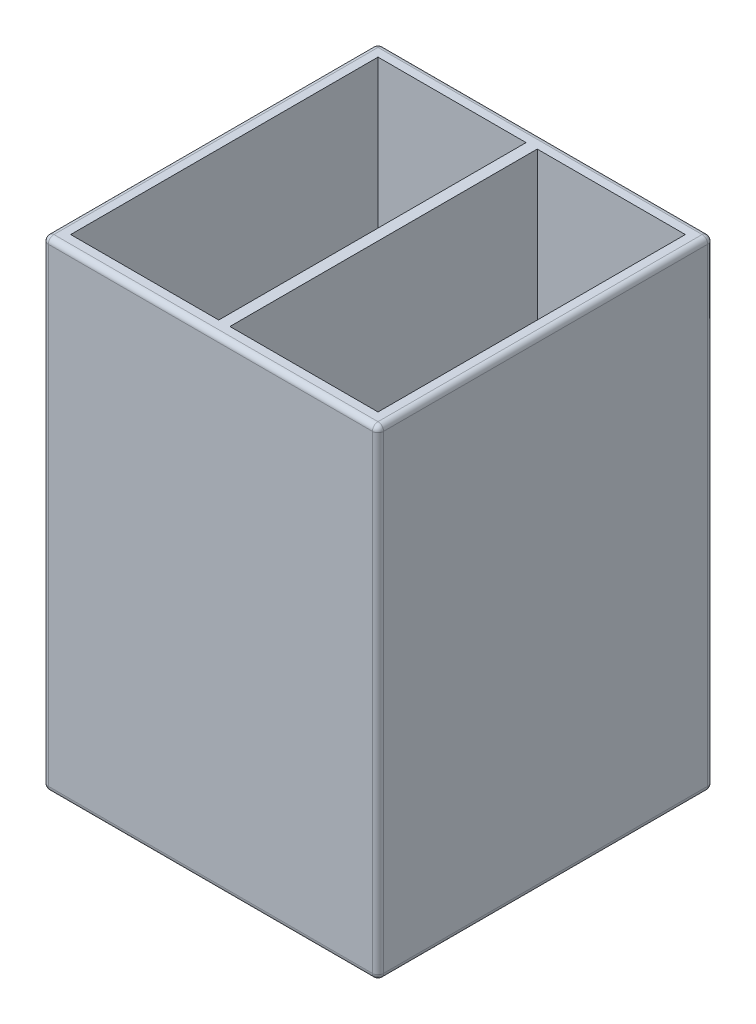
SolidWorks part; units mm, degrees
ref_plane "Front Plane" through (0, 0, 0) normal (0, 0, 1) x (1, 0, 0)
ref_plane "Top Plane" through (0, 0, 0) normal (0, 1, 0) x (1, 0, 0)
ref_plane "Right Plane" through (0, 0, 0) normal (1, 0, 0) x (0, 0, -1)
sketch "Sketch3" plane through (0, 0, 0) normal (0, 1, 0) x (1, 0, 0)
  line L1 (-164.0002, 4.2753) -> (-87.8002, 4.2753)
  line L2 (-164.0002, 4.2753) -> (-164.0002, -71.9247)
  line L3 (-164.0002, -71.9247) -> (-87.8002, -71.9247)
  line L4 (-87.8002, 4.2753) -> (-87.8002, -71.9247)
  dimension "D1" = 76.2
  dimension "D2" = 76.2
extrude "Boss-Extrude1" add sketch "Sketch3" along normal blind 109.22
sketch "Sketch4" plane through (0, 109.22, 0) normal (0, 1, 0) x (1, 0, 0)
  line L0 (-87.8002, -71.9247) -> (-87.8002, 4.2753) construction
  line L2 (-160.8252, 1.1003) -> (-160.8252, -68.7497)
  line L4 (-90.9752, 1.1003) -> (-90.9752, -68.7497)
  line L6 (-160.8252, 1.1003) -> (-127.1702, 1.1003)
  line L8 (-127.1702, 1.1003) -> (-127.1702, -68.7497)
  line L10 (-124.6302, 1.1003) -> (-124.6302, -68.7497)
  line L11 (-124.6302, 1.1003) -> (-90.9752, 1.1003)
  line L12 (-160.8252, -68.7497) -> (-127.1702, -68.7497)
  line L13 (-124.6302, -68.7497) -> (-90.9752, -68.7497)
  dimension "D1" = 69.85
  dimension "D2" = 69.85
  dimension "D3" = 3.175
  dimension "D5" = 2.54
  dimension "D6" = 33.655
  dimension "D7" = 69.85
extrude "Cut-Extrude2" cut sketch "Sketch4" against normal blind 101.6 contours L12 L8 L6 L2 | L13 L4 L11 L10
fillet "Fillet10" radius 1.27 13 edges at (-87.8002, 109.22, 33.8247) (-87.8002, 0, 33.8247) (-87.8002, 54.61, -4.2753) (-125.9002, 109.22, -4.2753) (-125.9002, 0, -4.2753) (-125.9002, 109.22, 71.9247) (-87.8002, 54.61, 71.9247) (-125.9002, 0, 71.9247) (-164.0002, 54.61, -4.2753) (-164.0002, 109.22, 33.8247) (-164.0002, 54.61, 71.9247) (-164.0002, 0, 33.8247) (-124.6302, 7.62, 33.8247)
